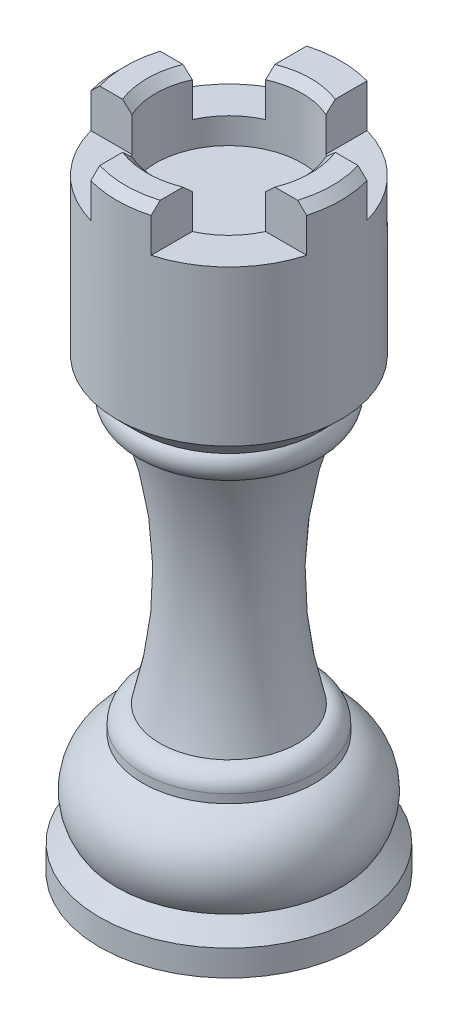
SolidWorks part; units mm, degrees
ref_plane "Ön Düzlem" through (0, 0, 0) normal (0, 0, 1) x (1, 0, 0)
ref_plane "Üst Düzlem" through (0, 0, 0) normal (0, 1, 0) x (1, 0, 0)
ref_plane "Sağ Düzlem" through (0, 0, 0) normal (1, 0, 0) x (0, 0, -1)
sketch "Çizim1" plane through (0, 0, 0) normal (0, 0, 1) x (1, 0, 0)
  line L0 (0, 78.1465) -> (0, -3.4681) construction
  line L1 (0, 0) -> (-15, 0)
  line L2 (-15, 0) -> (-15, 3)
  line L3 (-15, 3) -> (-13, 5)
  line L4 (-13, 70) -> (-13, 75)
  line L5 (-13, 75) -> (-8.5, 75)
  line L6 (-10, 13.97) -> (-10, 14.97)
  line L7 (-8.5, 75) -> (-8.5, 70)
  line L10 (0, 67) -> (-8.5, 67)
  line L11 (-8.5, 67) -> (-8.5, 70)
  line L13 (-13, 70) -> (-13, 52)
  line L14 (-13, 52) -> (-10.5, 49.5)
  line L18 (0, 67) -> (0, 0)
  arc A0 (-10, 13.97) -> (-13, 5) centre (-7.9981, 8.3138) ccw
  arc A1 (-10, 14.97) -> (-8, 16.97) centre (-8, 14.97) cw
  arc A2 (-10.5, 49.5) -> (-8.8928, 46.18) centre (-9, 48.1771) ccw
  arc A3 (-8.8928, 46.18) -> (-8, 16.97) centre (-56.2414, 30.1142) cw
  dimension "D10" = 6
  dimension "D11" = 13
  dimension "D15" = 8.5
  dimension "D17" = 3
  dimension "D14" = 2
  dimension "D21" = 50
  dimension "D3" = 5
  dimension "D4" = 15
  dimension "D7" = 1
  dimension "D20" = 9
revolve "Döndür1" add sketch "Çizim1" angle 360 about L0
sketch "Çizim3" plane through (0, 75, 0) normal (0, 1, 0) x (1, 0, 0)
  line L0 (-12.52, 3.5) -> (-7.746, 3.5)
  line L1 (-12.52, -3.5) -> (-7.746, -3.5)
  line L2 (7.746, -3.5) -> (12.52, -3.5)
  line L3 (12.52, 3.5) -> (7.746, 3.5)
  line L4 (-3.5, -12.52) -> (-3.5, -7.746)
  line L5 (3.5, -12.52) -> (3.5, -7.746)
  line L6 (3.5, 12.52) -> (3.5, 7.746)
  line L7 (-3.5, 12.52) -> (-3.5, 7.746)
  arc A0 (-3.5, 7.746) -> (-7.746, 3.5) centre (0, 0) ccw
  arc A1 (-3.5, 12.52) -> (-12.52, 3.5) centre (0, 0) ccw
  arc A2 (3.5, -7.746) -> (7.746, -3.5) centre (0, 0) ccw
  arc A3 (3.5, -12.52) -> (12.52, -3.5) centre (0, 0) ccw
  arc A4 (-7.746, -3.5) -> (-3.5, -7.746) centre (0, 0) ccw
  arc A5 (-12.52, -3.5) -> (-3.5, -12.52) centre (0, 0) ccw
  arc A6 (7.746, 3.5) -> (3.5, 7.746) centre (0, 0) ccw
  arc A7 (12.52, 3.5) -> (3.5, 12.52) centre (0, 0) ccw
  dimension "D2" = 17
  dimension "D3" = 26
  dimension "D1" = 3.5
  dimension "D4" = 3.5
  dimension "D5" = 3.5
  dimension "D6" = 3.5
  dimension "D7" = 7
  dimension "D8" = 7
extrude "Kes-Ekstrüzyon1" cut sketch "Çizim3" against normal blind 5
chamfer "Pah1" distance 1 angle 45 7 edges at (0, 75, 8.5) (8.5, 75, 0) (0, 75, 13) (13, 75, 0) (0, 75, -8.5) (-8.5, 75, 0) (-13, 75, 0)
